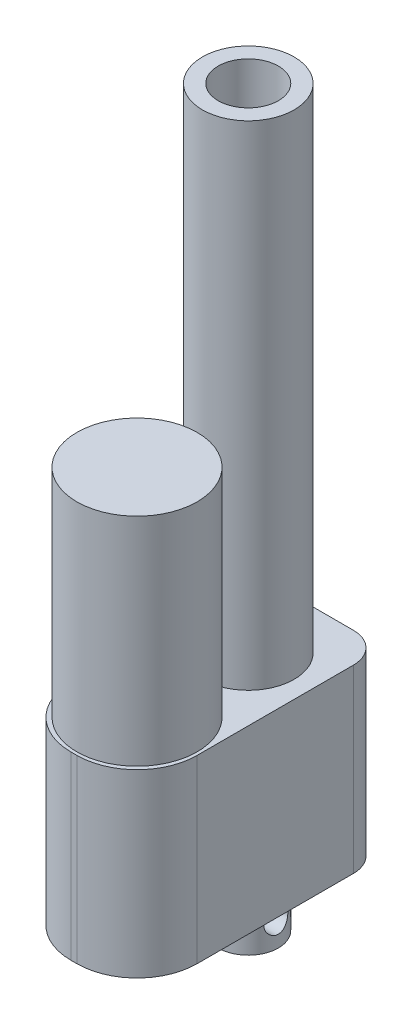
SolidWorks part; units mm, degrees
ref_plane "Front Plane" through (0, 0, 0) normal (0, 0, 1) x (1, 0, 0)
ref_plane "Top Plane" through (0, 0, 0) normal (0, 1, 0) x (1, 0, 0)
ref_plane "Right Plane" through (0, 0, 0) normal (1, 0, 0) x (0, 0, -1)
sketch "Sketch1" plane through (0, 0, 0) normal (0, 1, 0) x (1, 0, 0)
  circle A0 centre (0, 0) radius 15.25
extrude "Extrude1" add sketch "Sketch1" along normal blind 164
sketch "Sketch2" plane through (0, 0, 0) normal (0, -1, 0) x (1, 0, 0)
  line L0 (0, 24) -> (0, 36.1026) construction
  line L1 (-1, 58) -> (1, 58)
  line L2 (-21, 38) -> (-21, -24)
  line L3 (-21, -24) -> (21, -24)
  line L4 (21, 38) -> (21, -24)
  arc A0 (-1, 58) -> (-21, 38) centre (-1, 38) ccw
  arc A1 (21, 38) -> (1, 58) centre (1, 38) ccw
  point P0 (0, 0)
  dimension "D4" = 20
  dimension "D1" = 21
  dimension "D2" = 21
  dimension "D3" = 82
extrude "Extrude2" add sketch "Sketch2" along normal blind 60
sketch "Sketch3" plane through (0, 0, 0) normal (0, 1, 0) x (1, 0, 0)
  circle A0 centre (0, -37) radius 20
extrude "Extrude3" add sketch "Sketch3" along normal blind 72
sketch "Sketch4" plane through (0, -60, 0) normal (0, -1, 0) x (1, 0, 0)
  circle A0 centre (0, 0) radius 10
extrude "Extrude4" add sketch "Sketch4" along normal blind 20
sketch "Sketch5" plane through (0, 0, 0) normal (1, 0, 0) x (0, 0, -1)
  circle A0 centre (0, -72) radius 4
extrude "Extrude5" cut sketch "Sketch5" against normal mid plane 30
sketch "Sketch6" plane through (0, 164, 0) normal (0, 1, 0) x (1, 0, 0)
  circle A0 centre (0, 0) radius 10
extrude "Extrude6" cut sketch "Sketch6" against normal blind 150
fillet "Скругление1" radius 10 2 edges at (21, -30, -24) (-21, -30, -24)
